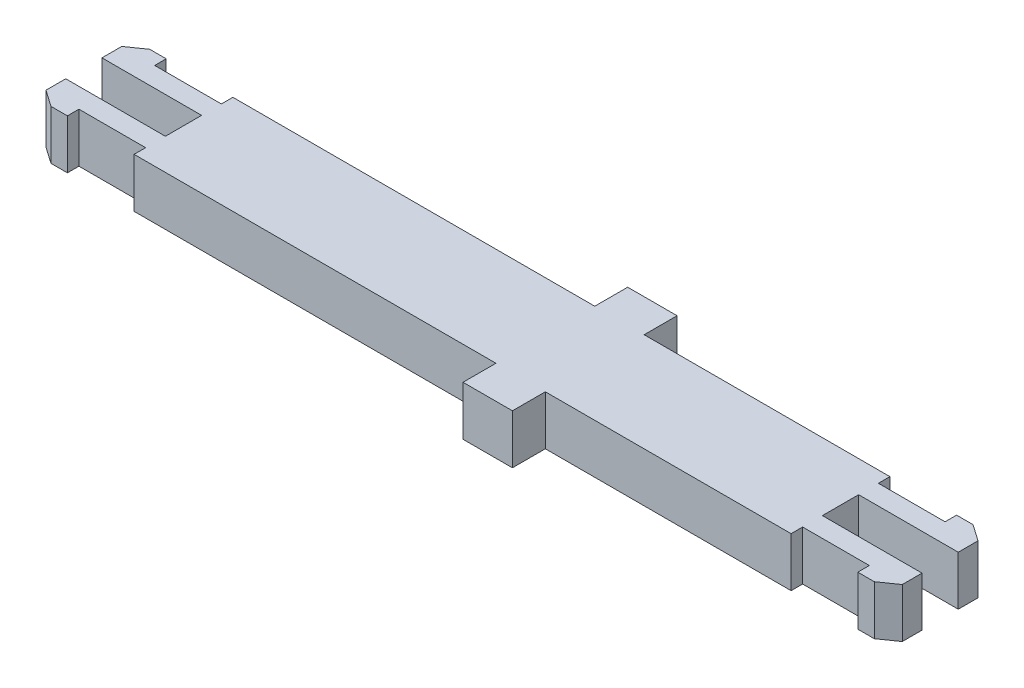
SolidWorks part; units mm, degrees
ref_plane "Front Plane" through (0, 0, 0) normal (0, 0, 1) x (1, 0, 0)
ref_plane "Top Plane" through (0, 0, 0) normal (0, 1, 0) x (1, 0, 0)
ref_plane "Right Plane" through (0, 0, 0) normal (1, 0, 0) x (0, 0, -1)
sketch "Sketch1" plane through (0, 0, 0) normal (0, 1, 0) x (1, 0, 0)
  line L0 (-19.95, 3) -> (2.025, 3)
  line L1 (2.025, 3) -> (2.025, 5)
  line L2 (2.025, 5) -> (5.025, 5)
  line L3 (5.025, 5) -> (5.025, 3)
  line L4 (5.025, 3) -> (19.95, 3)
  line L5 (19.95, 3) -> (19.95, 2.3)
  line L6 (19.95, 2.3) -> (24, 2.3)
  line L7 (24, 2.3) -> (24, 3)
  line L8 (24, 3) -> (25, 3)
  line L9 (25, 3) -> (26, 2.3)
  line L10 (26, 2.3) -> (26, 1.1)
  line L11 (26, 1.1) -> (19.95, 1.1)
  line L12 (19.95, 1.1) -> (19.95, -1.1)
  line L14 (-19.95, 0) -> (19.95, 0) construction
  line L15 (26, -1.1) -> (19.95, -1.1)
  line L16 (26, -2.3) -> (26, -1.1)
  line L17 (25, -3) -> (26, -2.3)
  line L18 (24, -3) -> (25, -3)
  line L19 (24, -2.3) -> (24, -3)
  line L20 (19.95, -2.3) -> (24, -2.3)
  line L21 (19.95, -3) -> (19.95, -2.3)
  line L22 (5.025, -3) -> (19.95, -3)
  line L23 (5.025, -5) -> (5.025, -3)
  line L24 (2.025, -5) -> (5.025, -5)
  line L25 (2.025, -3) -> (2.025, -5)
  line L26 (-19.95, -3) -> (2.025, -3)
  line L27 (2.025, 3) -> (24, 3) construction
  line L28 (5.025, 3) -> (19.95, 3) construction
  line L29 (0, 0) -> (0, 16.9595) construction
  line L30 (-19.95, -3) -> (-19.95, -2.3)
  line L31 (-19.95, -2.3) -> (-24, -2.3)
  line L32 (-24, -2.3) -> (-24, -3)
  line L33 (-24, -3) -> (-25, -3)
  line L34 (-25, -3) -> (-26, -2.3)
  line L35 (-26, -2.3) -> (-26, -1.1)
  line L36 (-26, -1.1) -> (-19.95, -1.1)
  line L37 (-19.95, 1.1) -> (-19.95, -1.1)
  line L38 (-26, 1.1) -> (-19.95, 1.1)
  line L39 (-26, 2.3) -> (-26, 1.1)
  line L40 (-25, 3) -> (-26, 2.3)
  line L41 (-24, 3) -> (-25, 3)
  line L42 (-24, 2.3) -> (-24, 3)
  line L43 (-19.95, 2.3) -> (-24, 2.3)
  line L44 (-19.95, 3) -> (-19.95, 2.3)
  dimension "D1" = 6
  dimension "D2" = 6
  dimension "D3" = 2.2
  dimension "D4" = 4.6
  dimension "D5" = 4.05
  dimension "D6" = 1
  dimension "D7" = 1
  dimension "D8" = 48
  dimension "D9" = 10
  dimension "D10" = 3
extrude "Boss-Extrude1" add sketch "Sketch1" along normal blind 3 contours L0 L1 L2 L3 L4 L5 L6 L7 L8 L9 L10 L11 L12 L15 L16 L17 L18 L19 L20 L21 L22 L23 L24 L25 L26 L30 L31 L32 L33 L34 L35 L36 L37 L38 L39 L40 L41 L42 L43 L44
